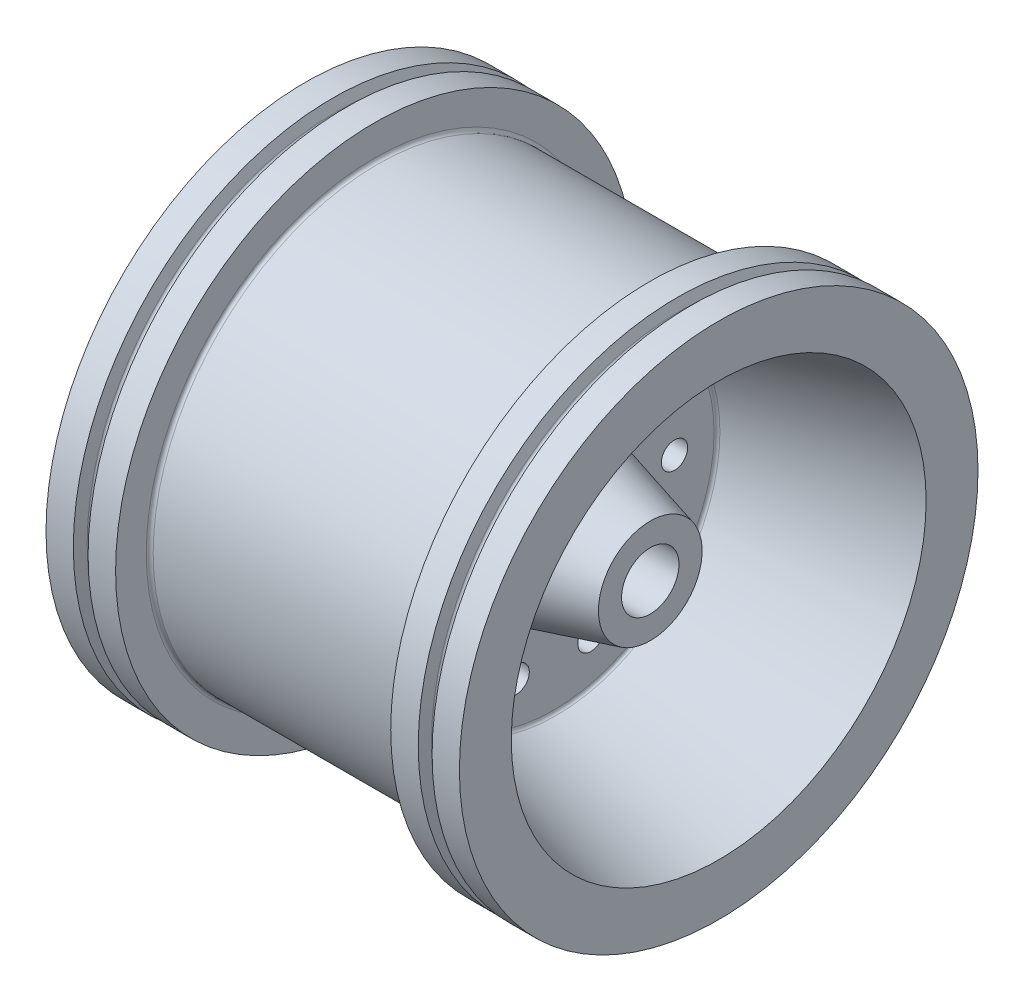
SolidWorks part; units mm, degrees
material "1060 Alloy"
ref_plane "Front Plane" through (0, 0, 0) normal (0, 0, 1) x (1, 0, 0)
ref_plane "Top Plane" through (0, 0, 0) normal (0, 1, 0) x (1, 0, 0)
ref_plane "Right Plane" through (0, 0, 0) normal (1, 0, 0) x (0, 0, -1)
sketch "Sketch1" plane through (0, 0, 0) normal (0, 0, 1) x (1, 0, 0)
  line L0 (-439.5428, 0) -> (21537.5969, 0) construction
  line L1 (0, 0) -> (0, 132.5905) construction
  line L2 (-12, 65) -> (12, 65)
  line L3 (12, 65) -> (39.7913, 65)
  line L4 (39.7913, 65) -> (39.7913, 74.8696)
  line L5 (39.7913, 74.8696) -> (47.7505, 74.8696)
  line L6 (47.7505, 74.8696) -> (49.7913, 69.943)
  line L7 (49.7913, 69.943) -> (51.8858, 75)
  line L8 (51.8858, 75) -> (59.7913, 75)
  line L9 (59.7913, 75) -> (59.7913, 60)
  line L10 (59.7913, 60) -> (12.0096, 47.1969)
  line L11 (12.0096, 47.1969) -> (12.0096, 22.5)
  line L12 (12.0096, 22.5) -> (40, 15)
  line L13 (40, 15) -> (40, 8.3086)
  line L14 (40, 8.3086) -> (-40, 8.3086)
  line L15 (-40, 15) -> (-40, 8.3086)
  line L16 (-12.0096, 22.5) -> (-40, 15)
  line L17 (-12.0096, 47.1969) -> (-12.0096, 22.5)
  line L18 (-59.7913, 60) -> (-12.0096, 47.1969)
  line L19 (-59.7913, 75) -> (-59.7913, 60)
  line L20 (-51.8858, 75) -> (-59.7913, 75)
  line L21 (-49.7913, 69.943) -> (-51.8858, 75)
  line L22 (-47.7505, 74.8696) -> (-49.7913, 69.943)
  line L23 (-39.7913, 74.8696) -> (-47.7505, 74.8696)
  line L24 (-39.7913, 65) -> (-39.7913, 74.8696)
  line L25 (-12, 65) -> (-39.7913, 65)
  point P20 (0, 8.3086)
  point P31 (0, 65)
  dimension "D2" = 60
  dimension "D3" = 65
  dimension "D4" = 20
  dimension "D5" = 45
  dimension "D6" = 360
  dimension "D8" = 30
  dimension "D9" = 45
  dimension "D10" = 120
  dimension "D11" = 150
  dimension "D12" = 15
  dimension "D13" = 15
  dimension "D14" = 80
  dimension "D15" = 90
  dimension "D16" = 12
revolve "Revolve1" add sketch "Sketch1" angle 360 about L0
sketch "Sketch2" plane through (12.0096, 0, 0) normal (1, 0, 0) x (0, 0, -1)
  circle A1 centre (0, 0) radius 35 construction
  circle A2 centre (33.7317, -9.3365) radius 0.1676 construction
  point P6 (35, 0)
  dimension "D1" = 70
hole_wizard "3/8 (0.3) Diameter Hole1" positions "Sketch2" profile "Sketch3" hole size "3/8" standard "ANSI Inch" end condition through all
sketch "Sketch3" plane through (12.0096, 0, -35) normal (0, 1, 0) x (0, 0, -1)
  line L0 (0, 0) -> (0, 71.8009)
  line L1 (0, 71.8009) -> (3.81, 71.8009)
  line L2 (3.81, 71.8009) -> (3.81, 0)
  line L5 (3.81, 0) -> (0, 0)
  line L11 (0, -6.35) -> (0, 107.95) construction
  dimension "Thru Hole Dia." = 7.62
  dimension "Thru Hole Depth" = 71.8009
pattern_circular "CirPattern1" count 10 over 360 about axis through (0, 0, 0) along (1, 0, 0) of "3/8 (0.3) Diameter Hole1"
sketch "Sketch4" plane through (-40, 0, 0) normal (-1, 0, 0) x (0, 0, 1)
  circle A0 centre (0, 0) radius 10.75
  dimension "D1" = 21.5
extrude "Cut-Extrude1" cut sketch "Sketch4" against normal blind 6.9
fillet "Fillet1" radius 1 3 edges at (-12.0096, 0, 22.5) (-33.1, 0, 10.75) (-12.0096, 0, 47.1969)
fillet "Fillet2" radius 1 4 edges at (39.7913, 0, 65) (49.7913, 0, 69.943) (-49.7913, 0, 69.943) (-39.7913, 0, 65)
fillet "Fillet3" radius 1 2 edges at (12.0096, 0, 47.1969) (12.0096, 0, 22.5)
